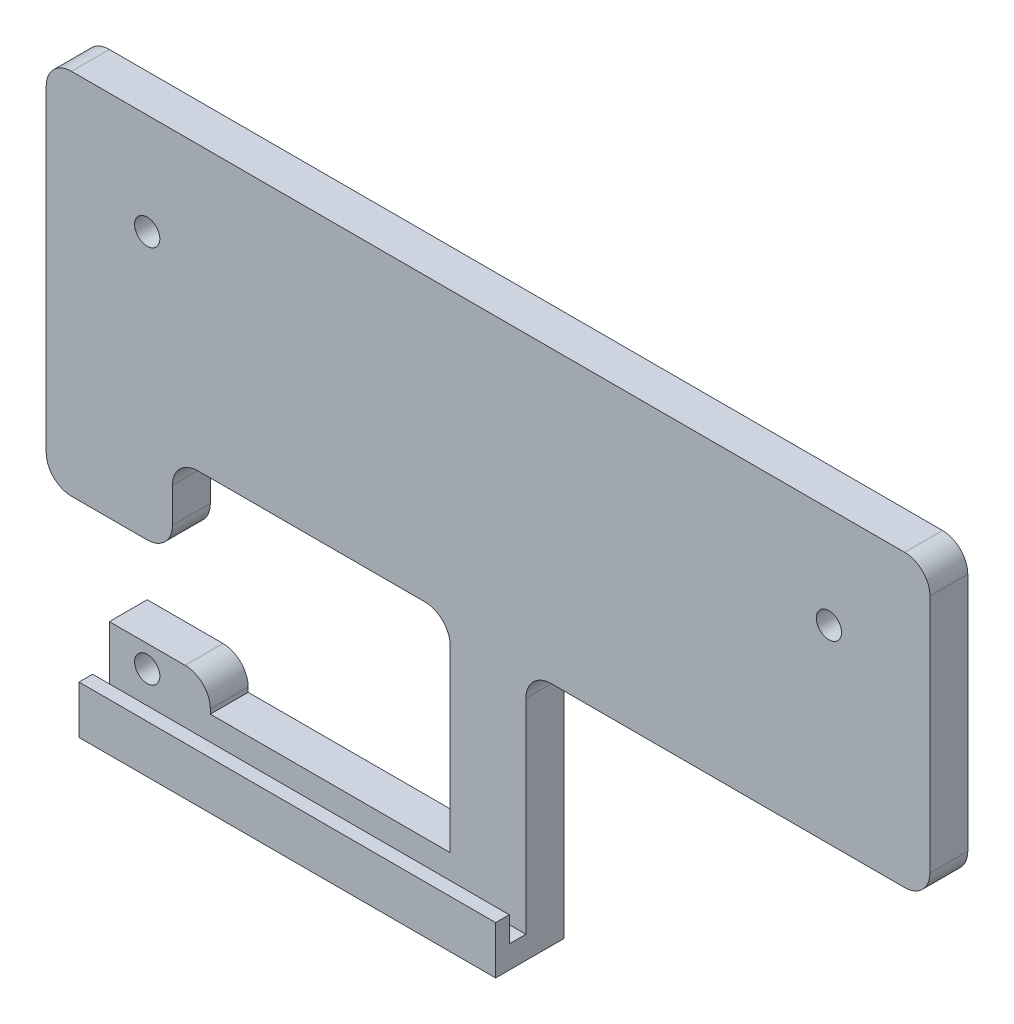
SolidWorks part; units mm, degrees
ref_plane "Front Plane" through (0, 0, 0) normal (0, 0, 1) x (1, 0, 0)
ref_plane "Top Plane" through (0, 0, 0) normal (0, 1, 0) x (1, 0, 0)
ref_plane "Right Plane" through (0, 0, 0) normal (1, 0, 0) x (0, 0, -1)
sketch "Sketch1" plane through (0, 0, 0) normal (0, 0, 1) x (1, 0, 0)
  line L0 (38.1, 22.86) -> (-38.1, 22.86) construction
  line L1 (-38.1, 22.86) -> (-38.1, -22.86) construction
  line L2 (-38.1, -22.86) -> (38.1, -22.86) construction
  line L3 (38.1, -22.86) -> (38.1, 22.86) construction
  line L4 (35.56, 22.86) -> (-35.56, 22.86) construction
  line L5 (-35.56, -22.86) -> (35.56, -22.86) construction
  line L6 (38.1, -20.32) -> (38.1, 20.32) construction
  line L7 (-38.1, 20.32) -> (-38.1, -9.3345) construction
  line L8 (0, 22.86) -> (0, -22.86) construction
  line L9 (-38.1, 0) -> (38.1, 0) construction
  line L10 (-38.1, -8.5725) -> (-38.1, -16.8275) construction
  line L11 (-38.1, -16.8275) -> (-33.528, -16.8275) construction
  line L12 (-33.528, -16.8275) -> (-33.528, -8.5725) construction
  line L13 (-33.528, -8.5725) -> (-38.1, -8.5725) construction
  line L14 (-34.29, -19.05) -> (34.29, -19.05) construction
  dimension "D1" = 0.762
  dimension "D2" = 0.762
  dimension "D3" = 4.572
sketch "Sketch2" plane through (0, 0, -1.651) normal (0, 0, -1) x (-1, 0, 0)
  line L1 (-30.48, 15.24) -> (-38.1, 15.24)
  line L2 (-30.48, 15.24) -> (-30.48, 22.86) construction
  line L4 (-38.1, 15.24) -> (-38.1, 22.86) construction
  line L5 (-30.48, 15.24) -> (-38.1, 22.86) construction
  line L6 (-30.48, 22.86) -> (-38.1, 15.24) construction
  line L9 (-29.464, 15.24) -> (-30.48, 15.24)
  line L11 (-44.45, 26.67) -> (-44.45, 5.3785)
  line L12 (-39.37, 4.953) -> (-29.464, 4.953)
  line L13 (-3.81, -2.54) -> (-3.81, -22.86)
  line L14 (38.1, -22.86) -> (-38.1, -22.86) construction
  line L16 (38.1, -22.86) -> (38.1, -16.8275)
  line L17 (38.1, -16.8275) -> (30.48, -16.8275)
  line L18 (27.94, -19.3675) -> (27.94, -19.812)
  line L19 (27.94, -19.812) -> (3.81, -19.812)
  line L20 (3.81, -19.812) -> (3.81, -1.778)
  line L21 (6.35, 0.762) -> (29.21, 0.762)
  line L24 (-38.1, 15.24) -> (-39.37, 15.24)
  line L25 (-39.37, 15.24) -> (-39.37, 4.953)
  line L26 (-44.45, 5.3785) -> (-44.45, 2.54)
  line L27 (-41.91, 0) -> (-6.35, 0)
  line L29 (44.45, 26.67) -> (44.45, -5.2705)
  line L30 (41.91, -7.8105) -> (34.29, -7.8105)
  line L31 (31.75, -5.2705) -> (31.75, -1.778)
  line L32 (-29.464, 15.24) -> (-29.464, 4.953)
  line L33 (-3.81, -22.86) -> (-3.81, -25.4)
  line L35 (38.1, -25.4) -> (38.1, -22.86)
  line L36 (-38.1, -22.86) -> (-38.1, 22.86) construction
  line L37 (-30.734, 14.605) -> (-30.734, 5.715) construction
  line L39 (-30.734, 5.715) -> (-38.1, 5.715) construction
  line L40 (38.1, 22.86) -> (38.1, -22.86) construction
  line L41 (33.528, -8.5725) -> (38.1, -8.5725) construction
  line L42 (34.29, -19.05) -> (-34.29, -19.05) construction
  line L43 (0, 22.86) -> (0, -22.86) construction
  line L44 (38.1, 0) -> (-38.1, 0) construction
  line L45 (-3.81, -25.4) -> (38.1, -25.4)
  line L46 (-38.1, 22.86) -> (-30.48, 22.86) construction
  line L47 (-41.91, 29.21) -> (41.91, 29.21)
  line L48 (-35.56, 22.86) -> (35.56, 22.86) construction
  arc A0 (-44.45, 2.54) -> (-41.91, 0) centre (-41.91, 2.54) ccw
  arc A3 (44.45, -5.2705) -> (41.91, -7.8105) centre (41.91, -5.2705) cw
  arc A4 (-6.35, 0) -> (-3.81, -2.54) centre (-6.35, -2.54) cw
  arc A5 (30.48, -16.8275) -> (27.94, -19.3675) centre (30.48, -19.3675) ccw
  arc A6 (34.29, -7.8105) -> (31.75, -5.2705) centre (34.29, -5.2705) cw
  arc A7 (31.75, -1.778) -> (29.21, 0.762) centre (29.21, -1.778) ccw
  arc A8 (3.81, -1.778) -> (6.35, 0.762) centre (6.35, -1.778) cw
  arc A9 (44.45, 26.67) -> (41.91, 29.21) centre (41.91, 26.67) ccw
  arc A10 (-44.45, 26.67) -> (-41.91, 29.21) centre (-41.91, 26.67) cw
  point P0 (-34.29, 19.05)
  point P41 (-44.45, 3.9592)
  dimension "D14" = 2.54
  dimension "D16" = 2.54
  dimension "D1" = 1.27
  dimension "D2" = 1.27
  dimension "D3" = 0.762
  dimension "D4" = 6.35
  dimension "D5" = 6.35
  dimension "D6" = 0.762
  dimension "D7" = 0.762
  dimension "D8" = 10.16
  dimension "D9" = 3.81
  dimension "D10" = 3.81
  dimension "D11" = 2.54
  dimension "D12" = 0.762
  dimension "D13" = 6.35
  dimension "D15" = 6.35
extrude "Boss-Extrude1" add sketch "Sketch2" along normal blind 3.81 from surface at 0 contours L45 L35 L16 L17 A5 L18 L19 L20 A8 L21 A7 L31 A6 L30 A3 L29 A9 L47 A10 L11 L26 A0 L27 A4 L13 L33
sketch "Sketch3" plane through (0, 0, -1.651) normal (0, 0, 1) x (1, 0, 0)
  line L0 (-38.1, -23.114) -> (3.81, -23.114)
  line L1 (-38.1, -25.4) -> (-38.1, -16.8275) construction
  line L2 (3.81, -2.54) -> (3.81, -25.4) construction
  line L3 (3.81, -23.114) -> (3.81, -25.4)
  line L4 (3.81, -25.4) -> (-38.1, -25.4)
  line L5 (-38.1, -25.4) -> (-38.1, -23.114)
  line L6 (-38.1, -22.86) -> (38.1, -22.86) construction
  dimension "D1" = 0.254
extrude "Boss-Extrude2" add sketch "Sketch3" along normal blind 3.048
sketch "Sketch4" plane through (0, -23.114, 0) normal (0, 1, 0) x (1, 0, 0)
  line L0 (3.81, -0.0254) -> (-38.1, -0.0254)
  line L1 (3.81, -1.397) -> (3.81, 1.651) construction
  line L2 (-38.1, -1.397) -> (-38.1, 1.651) construction
  line L3 (-38.1, -0.0254) -> (-38.1, -1.397)
  line L4 (-38.1, -1.397) -> (3.81, -1.397)
  line L5 (3.81, -1.397) -> (3.81, -0.0254)
  line L6 (-34.29, 0) -> (34.29, 0) construction
  dimension "D1" = 0.0254
extrude "Boss-Extrude3" add sketch "Sketch4" along normal blind 2.54
sketch "Sketch5" plane through (0, 0, -1.651) normal (0, 0, 1) x (1, 0, 0)
  circle A0 centre (-34.29, 19.05) radius 1.27
  circle A1 centre (34.29, 19.05) radius 1.27
  circle A2 centre (-34.29, -19.05) radius 1.27
  dimension "D1" = 2.54
extrude "Cut-Extrude1" cut sketch "Sketch5" against normal through all both and the other way through all
